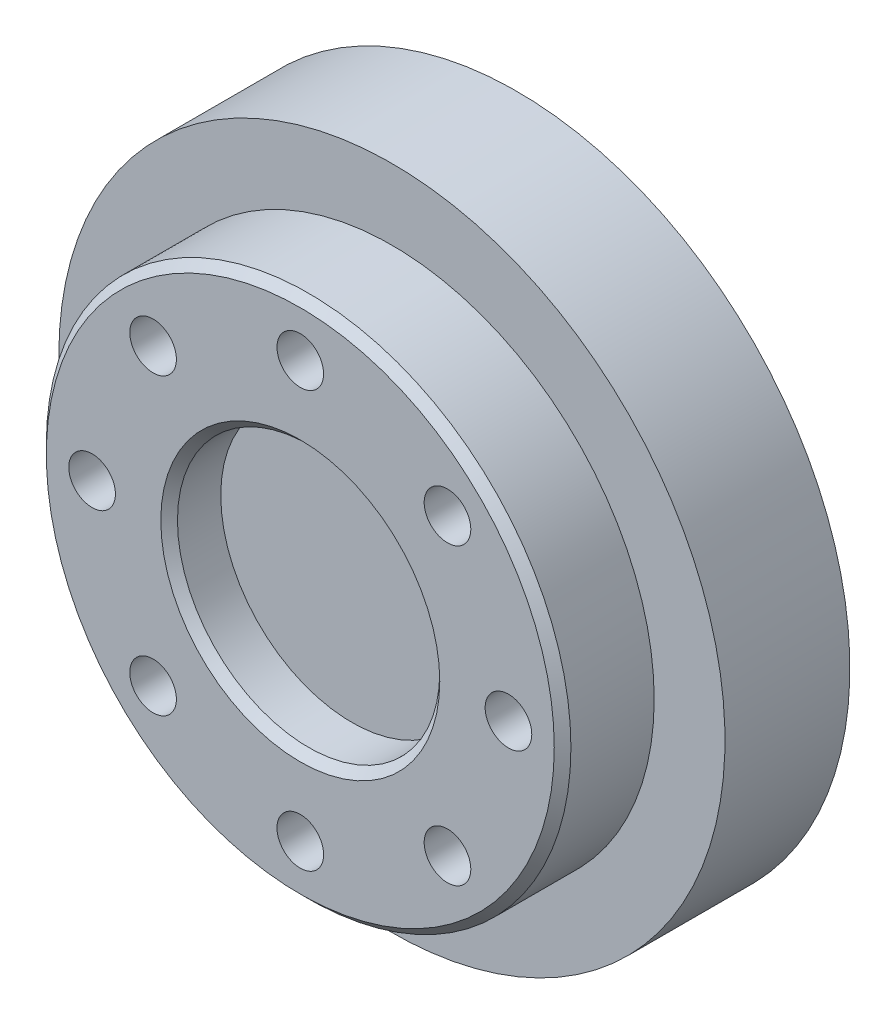
SolidWorks part; units mm, degrees
ref_plane "Front Plane" through (0, 0, 0) normal (0, 0, 1) x (1, 0, 0)
ref_plane "Top Plane" through (0, 0, 0) normal (0, 1, 0) x (1, 0, 0)
ref_plane "Right Plane" through (0, 0, 0) normal (1, 0, 0) x (0, 0, -1)
sketch "Sketch1" plane through (0, 0, 0) normal (0, 0, 1) x (1, 0, 0)
  circle A0 centre (0, 0) radius 31.5
  circle A2 centre (0, 25) radius 2.8
  circle A3 centre (17.6777, 17.6777) radius 2.8
  circle A4 centre (25, 0) radius 2.8
  circle A5 centre (17.6777, -17.6777) radius 2.8
  circle A6 centre (0, -25) radius 2.8
  circle A7 centre (-17.6777, -17.6777) radius 2.8
  circle A8 centre (-25, 0) radius 2.8
  circle A9 centre (-17.6777, 17.6777) radius 2.8
  circle A10 centre (0, 0) radius 15.75
  point P23 (0, 0)
  dimension "D1" = 8
extrude "Boss-Extrude1" add sketch "Sketch1" against normal blind 11 contours A0
ref_plane "Plane1" through (0, 0, 0) normal (0, 0, 1) x (1, 0, 0)
sketch "Sketch2" plane through (0, 0, 0) normal (0, 0, 1) x (1, 0, 0)
  circle A1 centre (0, 25) radius 2.8
  circle A2 centre (17.6777, 17.6777) radius 2.8
  circle A3 centre (25, 0) radius 2.8
  circle A4 centre (17.6777, -17.6777) radius 2.8
  circle A5 centre (0, -25) radius 2.8
  circle A6 centre (-17.6777, -17.6777) radius 2.8
  circle A7 centre (-25, 0) radius 2.8
  circle A8 centre (-17.6777, 17.6777) radius 2.8
  point P0 (0, 0)
  point P21 (0, 0)
  dimension "D1" = 8
extrude "Cut-Extrude5" cut sketch "Sketch2" against normal blind 9
sketch "Sketch4" plane through (0, 0, 0) normal (0, 0, 1) x (1, 0, 0)
  circle A0 centre (0, 0) radius 15.75
extrude "Cut-Extrude6" cut sketch "Sketch4" against normal blind 6.2
chamfer "Chamfer1" distance 1 angle 45 1 edges at (31.5, 0, 0)
chamfer "Chamfer2" distance 1 angle 45 1 edges at (15.75, 0, 0)
ref_plane "Plane2" through (0, 0, -11) normal (0, 0, -1) x (-1, 0, 0)
sketch "Sketch5" plane through (0, 0, -11) normal (0, 0, -1) x (-1, 0, 0)
  circle A0 centre (0, 0) radius 40
extrude "Boss-Extrude3" add sketch "Sketch5" along normal blind 15
